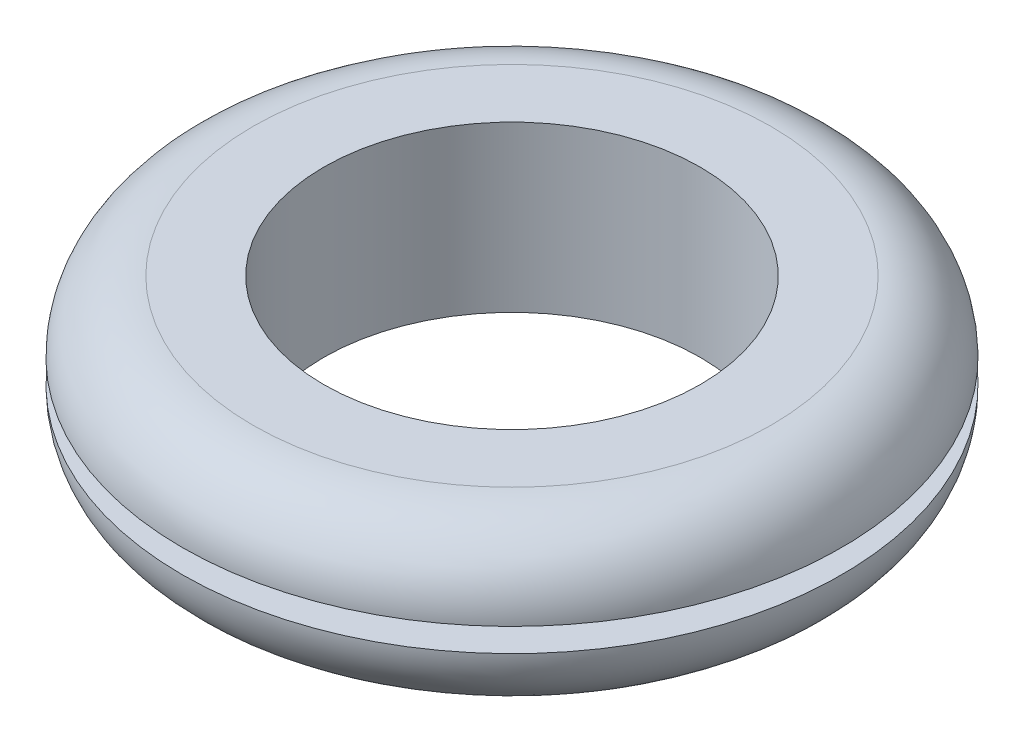
SolidWorks part; units mm, degrees
material "BUTYL"
ref_plane "Front" through (0, 0, 0) normal (0, 0, 1) x (1, 0, 0)
ref_plane "Top" through (0, 0, 0) normal (0, 1, 0) x (1, 0, 0)
ref_plane "Right" through (0, 0, 0) normal (1, 0, 0) x (0, 0, -1)
sketch "Sketch1" plane through (0, 0, 0) normal (0, 0, 1) x (1, 0, 0)
  line L0 (-12.7, 0) -> (12.7, 0) construction
  line L1 (-17.4625, 0) -> (17.4625, 0) construction
  line L2 (0, 5.5562) -> (0, -5.5562) construction
  line L3 (22.225, 5.5563) -> (-22.225, 5.5562) construction
  line L4 (17.4625, 0.7937) -> (17.4625, -0.7937) construction
  dimension "ID" = 25.4
  dimension "for hole dia" = 34.925
  dimension "oall ht" = 11.1125
  dimension "flange dia" = 44.45
  dimension "material thick" = 1.5875
sketch "Sketch2" plane through (0, 0, 0) normal (0, 0, 1) x (1, 0, 0)
  line L0 (17.4625, 0.7937) -> (22.225, 0.7938)
  line L1 (22.225, 5.5563) -> (22.225, -5.5562) construction
  line L2 (22.225, 5.5563) -> (-22.225, 5.5563) construction
  line L3 (12.7, 5.5563) -> (17.4625, 5.5563)
  line L4 (17.4625, 0.7937) -> (17.4625, -0.7937)
  line L5 (12.7, 5.5563) -> (12.7, -5.5562)
  line L6 (12.7, -5.5562) -> (17.4625, -5.5563)
  line L7 (22.225, -0.7937) -> (17.4625, -0.7937)
  arc A0 (17.4625, 5.5563) -> (22.225, 0.7938) centre (17.4625, 0.7937) cw
  arc A1 (17.4625, -5.5563) -> (22.225, -0.7937) centre (17.4625, -0.7937) ccw
revolve "Revolve1" add sketch "Sketch2" angle 360 about L2
